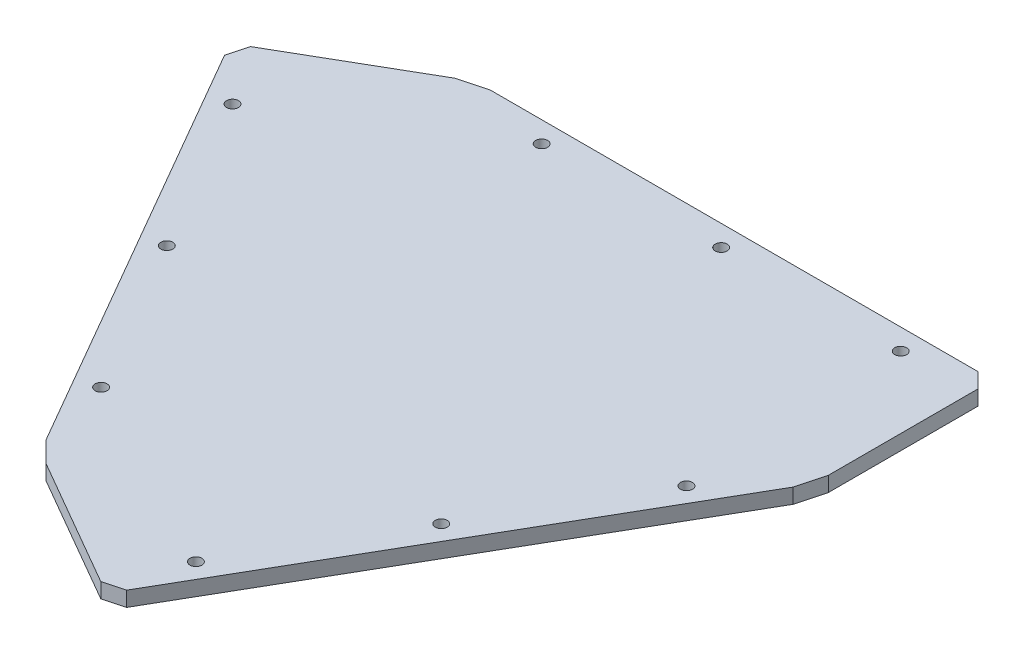
SolidWorks part; units mm, degrees
material "PVC rigide"
ref_plane "Plan de face" through (0, 0, 0) normal (0, 0, 1) x (1, 0, 0)
ref_plane "Plan de dessus" through (0, 0, 0) normal (0, 1, 0) x (1, 0, 0)
ref_plane "Plan de droite" through (0, 0, 0) normal (1, 0, 0) x (0, 0, -1)
sketch "Esquisse1" plane through (0, 0, 0) normal (0, 1, 0) x (1, 0, 0)
  line L0 (-64.1795, 79.9408) -> (98.8205, 79.9408)
  line L6 (-118.641, 45.6107) -> (-37.141, -95.5515)
  line L7 (19.8205, -125.5515) -> (101.3205, 15.6107)
  line L8 (-73.5096, 77.4408) -> (-116.8109, 52.4408)
  line L9 (103.8205, 74.9408) -> (103.8205, 24.9408)
  line L10 (12.9904, -127.3816) -> (-30.3109, -102.3816)
  line L11 (-69.1795, 79.9408) -> (-138.4615, 79.9408) construction
  line L12 (-121.141, 49.9408) -> (-138.4615, 79.9408) construction
  line L13 (-34.641, -99.8816) -> (0, -159.8816) construction
  line L14 (17.3205, -129.8816) -> (0, -159.8816) construction
  line L15 (103.8205, 79.9408) -> (138.4615, 79.9408) construction
  line L16 (103.8205, 19.9408) -> (138.4615, 79.9408) construction
  line L17 (0, -159.8816) -> (0, 79.9408) construction
  line L18 (-138.4615, 79.9408) -> (69.2308, -39.9704) construction
  line L19 (-69.2308, -39.9704) -> (138.4615, 79.9408) construction
  line L20 (12.9904, -127.3816) -> (19.8205, -125.5515)
  line L21 (17.3205, -129.8816) -> (19.8205, -125.5515) construction
  line L22 (-121.141, 49.9408) -> (-118.641, 45.6107) construction
  line L23 (-116.8109, 52.4408) -> (-118.641, 45.6107)
  line L24 (103.8205, 79.9408) -> (98.8205, 79.9408) construction
  line L25 (103.8205, 74.9408) -> (98.8205, 79.9408)
  line L26 (-30.3109, -102.3816) -> (-37.141, -95.5515)
  line L27 (-34.641, -99.8816) -> (-37.141, -95.5515) construction
  line L28 (-30.3109, -102.3816) -> (-34.641, -99.8816) construction
  line L29 (-73.5096, 77.4408) -> (-69.1795, 79.9408) construction
  line L30 (-69.1795, 79.9408) -> (-64.1795, 79.9408) construction
  line L31 (-73.5096, 77.4408) -> (-64.1795, 79.9408)
  line L32 (103.8205, 24.9408) -> (103.8205, 19.9408) construction
  line L33 (103.8205, 19.9408) -> (101.3205, 15.6107) construction
  line L34 (103.8205, 24.9408) -> (101.3205, 15.6107)
  point P12 (0, 0)
  point P24 (0, 0)
  point P34 (0, 0)
  dimension "D1" = 90
  dimension "D2" = 90
  dimension "D3" = 90
  dimension "D4" = 173
  dimension "D5" = 60
  dimension "D6" = 5
  dimension "D7" = 5
  dimension "D9" = 5
  dimension "D10" = 5
  dimension "D8" = 3
  dimension "D11" = 3
extrude "Extrusion1" add sketch "Esquisse1" along normal blind 5
sketch "Esquisse8" plane through (0, 5, 0) normal (0, 1, 0) x (1, 0, 0)
  line L0 (-119.3693, 60.8721) -> (9.233, -161.8736) construction
  line L1 (-118.641, 45.6107) -> (-37.141, -95.5515) construction
  line L2 (-63.1686, -36.4704) -> (0, 0) construction
  line L3 (-69.2308, -39.9704) -> (138.4615, 79.9408) construction
  circle A0 centre (-103.1686, 32.8116) radius 2
  circle A1 centre (80, 72.9408) radius 2
  circle A2 centre (20, 72.9408) radius 2
  circle A3 centre (-73.1686, -19.1499) radius 2
  circle A4 centre (-43.1686, -71.1114) radius 2
  circle A5 centre (-40, 72.9408) radius 2
  circle A6 centre (23.1686, -105.7524) radius 2
  circle A7 centre (53.1686, -53.7909) radius 2
  circle A8 centre (83.1686, -1.8294) radius 2
  point P29 (0, 0)
  point P77 (0, 0)
  dimension "D2" = 4
  dimension "D4" = 60
  dimension "D1" = 7
  dimension "D3" = 60
  dimension "D5" = 20
  dimension "D6" = 3
extrude "Enlèv. mat.-Extru.14" cut sketch "Esquisse8" against normal up to next
